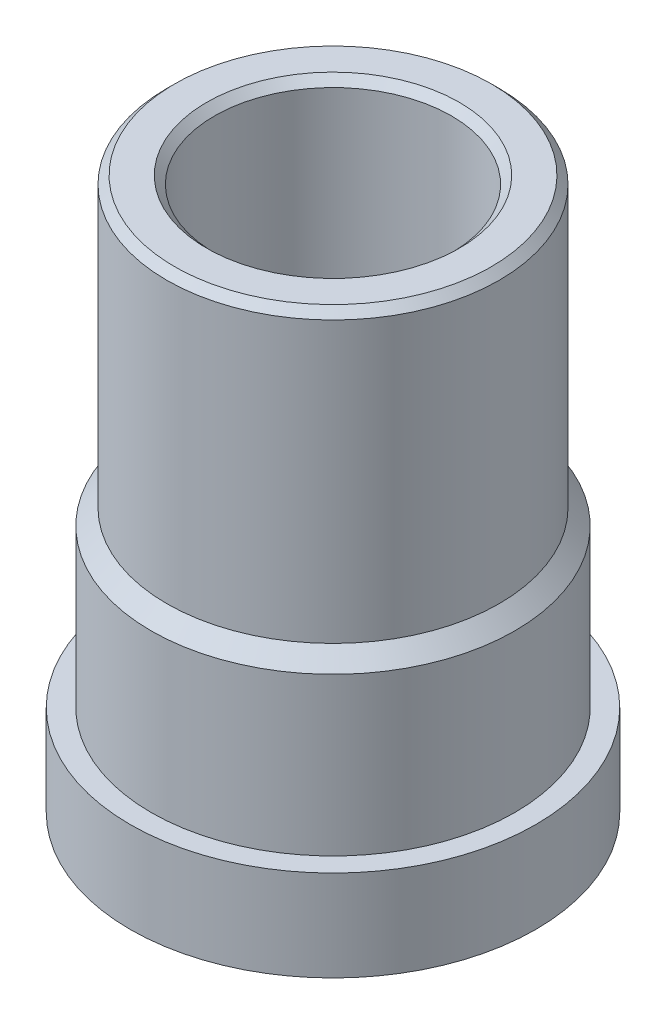
SolidWorks part; units mm, degrees
ref_plane "Спереди" through (0, 0, 0) normal (0, 0, 1) x (1, 0, 0)
ref_plane "Сверху" through (0, 0, 0) normal (0, 1, 0) x (1, 0, 0)
ref_plane "Справа" through (0, 0, 0) normal (1, 0, 0) x (0, 0, -1)
sketch "Эскиз1" plane through (0, 0, 0) normal (0, 0, 1) x (1, 0, 0)
  line L0 (0, 0) -> (0.915, 0)
  line L1 (0.915, 0) -> (0.915, 0.41)
  line L2 (0.915, 0.41) -> (0.8207, 0.41)
  line L3 (0.8207, 0.41) -> (0.8207, 1.12)
  line L4 (0.8207, 1.12) -> (0.75, 1.1907)
  line L5 (0.75, 1.1907) -> (0.75, 2.4546)
  line L6 (0.75, 2.4546) -> (0.7146, 2.49)
  line L7 (0.7146, 2.49) -> (0.5704, 2.49)
  line L8 (0.5704, 2.49) -> (0.535, 2.4546)
  line L9 (0.535, 2.4546) -> (0.535, 1.4958)
  line L10 (0.535, 1.4958) -> (0, 1.4958)
  line L11 (0, 0) -> (0, 1.4958)
  dimension "D1" = 0.41
  dimension "D2" = 0.71
  dimension "D3" = 2.49
  dimension "D4" = 135
  dimension "D5" = 135
  dimension "D6" = 0.05
  dimension "D7" = 135
  dimension "D8" = 0.1
  dimension "D9" = 0.535
  dimension "D10" = 0.915
  dimension "D11" = 0.75
  dimension "D12" = 1.4958
revolve "Повернуть1" add sketch "Эскиз1" angle 360 about L11
sketch "Эскиз2" plane through (0, 0, 0) normal (0, 0, 1) x (1, 0, 0)
  line L0 (0, 2.49) -> (0, 3.49)
  line L1 (-0.915, 0) -> (0.915, 0) construction
  point P5 (0, 2.99)
  dimension "D1" = 3.49
  dimension "D2" = 2.49
  dimension "D3" = 2.99
